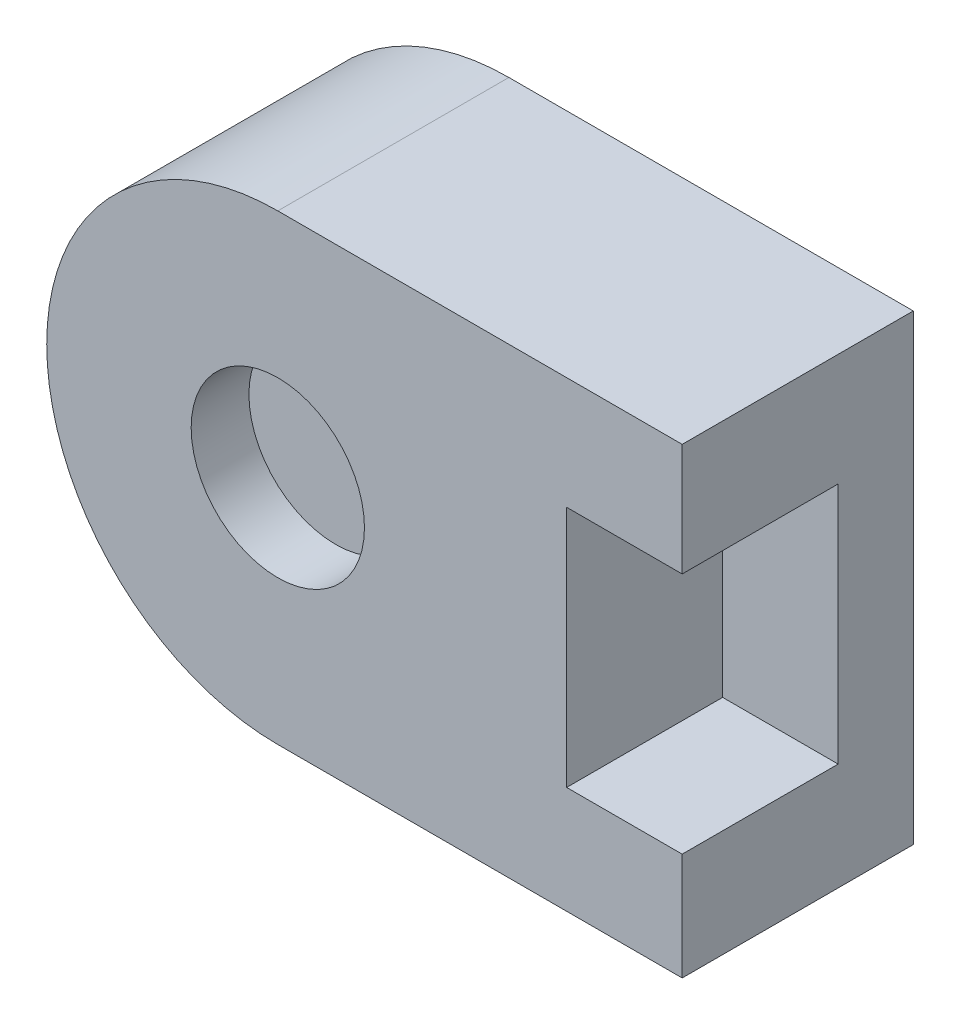
SolidWorks part; units mm, degrees
ref_plane "Front Plane" through (0, 0, 0) normal (0, 0, 1) x (1, 0, 0)
ref_plane "Top Plane" through (0, 0, 0) normal (0, 1, 0) x (1, 0, 0)
ref_plane "Right Plane" through (0, 0, 0) normal (1, 0, 0) x (0, 0, -1)
sketch "Sketch1" plane through (0, 0, 0) normal (0, 0, 1) x (1, 0, 0)
  line L0 (0, 40) -> (0, -40) construction
  line L1 (0, 40) -> (70, 40)
  line L2 (70, 40) -> (70, -40)
  line L3 (70, -40) -> (0, -40)
  arc A0 (0, 40) -> (0, -40) centre (0, 0) ccw
  dimension "D1" = 80
  dimension "D2" = 70
extrude "Boss-Extrude1" add sketch "Sketch1" along normal blind 40
sketch "Sketch2" plane through (0, 0, 40) normal (0, 0, 1) x (1, 0, 0)
  line L0 (0, 0) -> (70, 0) construction
  line L1 (70, -40) -> (70, 40) construction
  line L3 (50, 20.567) -> (70, 20.567)
  line L4 (50, 20.567) -> (50, -21.433)
  line L5 (50, -21.433) -> (70, -21.433)
  line L6 (70, 20.567) -> (70, -21.433)
  dimension "D1" = 20
  dimension "D2" = 42
extrude "Cut-Extrude1" cut sketch "Sketch2" against normal blind 27
sketch "Sketch3" plane through (0, 0, 40) normal (0, 0, 1) x (1, 0, 0)
  circle A0 centre (0, 0) radius 15
  dimension "D1" = 30
extrude "Cut-Extrude2" cut sketch "Sketch3" against normal blind 10
